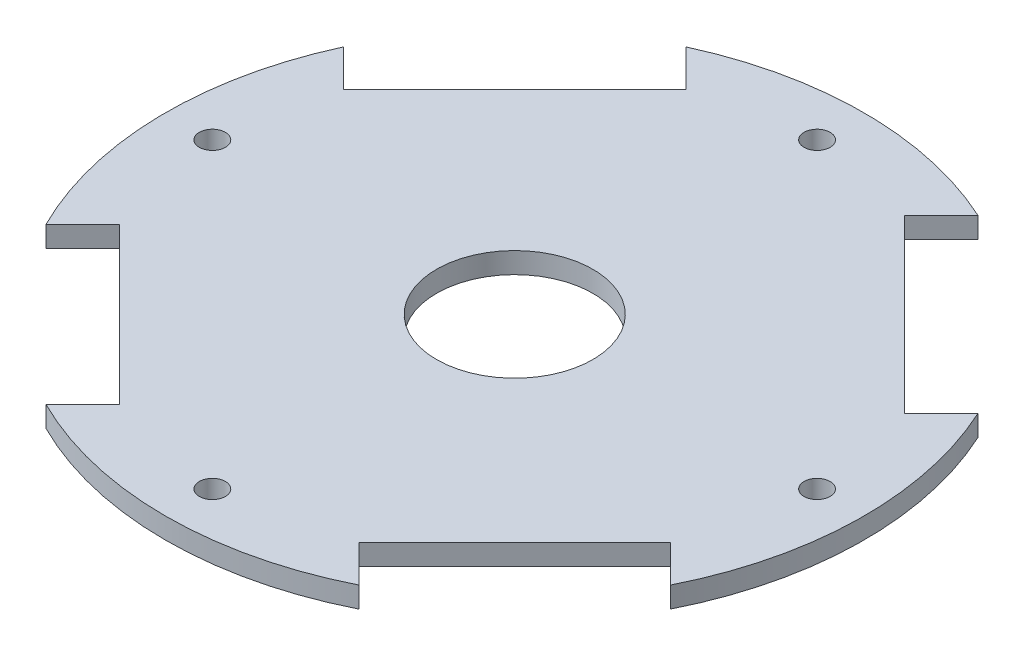
SolidWorks part; units mm, degrees
ref_plane "Front Plane" through (0, 0, 0) normal (0, 0, 1) x (1, 0, 0)
ref_plane "Top Plane" through (0, 0, 0) normal (0, 1, 0) x (1, 0, 0)
ref_plane "Right Plane" through (0, 0, 0) normal (1, 0, 0) x (0, 0, -1)
sketch "Sketch1" plane through (0, 0, 0) normal (0, 1, 0) x (1, 0, 0)
  circle A0 centre (0, 0) radius 67
  circle A1 centre (0, 58) radius 2.5
  circle A2 centre (58, 0) radius 2.5
  circle A3 centre (0, -58) radius 2.5
  circle A4 centre (-58, 0) radius 2.5
  point P10 (-21.3456, -19.7323)
  dimension "D1" = 58
extrude "Boss-Extrude1" add sketch "Sketch1" along normal blind 4 contours A0 A4 A3 A2 A1
sketch "Sketch2" plane through (0, 4, 0) normal (0, 1, 0) x (1, 0, 0)
  circle A0 centre (0, 0) radius 15
extrude "Cut-Extrude1" cut sketch "Sketch2" against normal blind 4
sketch "Sketch3" plane through (0, 4, 0) normal (0, 1, 0) x (1, 0, 0)
  line L0 (0, 58) -> (58, 0)
  line L1 (0, 58) -> (-58.0567, -0.0567)
  line L2 (58, 0) -> (-0.0567, -58.0567)
  line L3 (-58.0567, -0.0567) -> (-0.0567, -58.0567)
sketch "Sketch4" plane through (0, 0, 0) normal (0, -1, 0) x (1, 0, 0)
  line L0 (59.9083, 30) -> (52.8372, 22.9289)
  line L1 (30, 59.9083) -> (22.9289, 52.8372)
  line L2 (52.8372, 22.9289) -> (22.9289, 52.8372)
  line L3 (-59.9083, 30) -> (-52.8372, 22.9289)
  line L4 (-30, 59.9083) -> (-22.9289, 52.8372)
  line L5 (-52.8372, 22.9289) -> (-22.9289, 52.8372)
  line L6 (-53.7976, -20.9289) -> (-20.9289, -53.7976)
  line L7 (-28, -60.8687) -> (-20.9289, -53.7976)
  line L8 (-60.8687, -28) -> (-53.7976, -20.9289)
  line L9 (53.7976, -20.9289) -> (20.9289, -53.7976)
  line L10 (28, -60.8687) -> (20.9289, -53.7976)
  line L11 (60.8687, -28) -> (53.7976, -20.9289)
  arc A0 (-60.8687, -28) -> (-28, -60.8687) centre (0, 0) ccw
  arc A1 (-30, 59.9083) -> (-59.9083, 30) centre (0, 0) ccw
  arc A2 (59.9083, 30) -> (30, 59.9083) centre (0, 0) ccw
  arc A3 (28, -60.8687) -> (60.8687, -28) centre (0, 0) ccw
  dimension "D1" = 10
  dimension "D2" = 10
  dimension "D3" = 10
  dimension "D4" = 10
extrude "Cut-Extrude2" cut sketch "Sketch4" against normal blind 10
